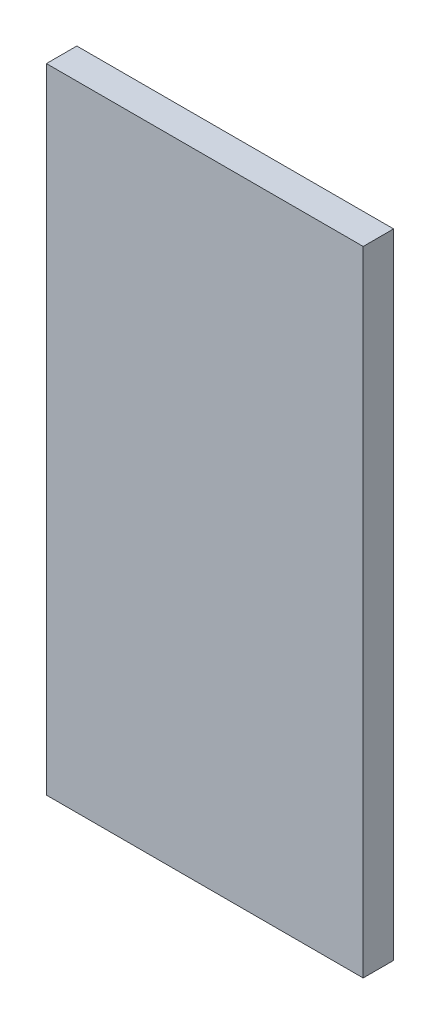
SolidWorks part; units mm, degrees
ref_plane "Front Plane" through (0, 0, 0) normal (0, 0, 1) x (1, 0, 0)
ref_plane "Top Plane" through (0, 0, 0) normal (0, 1, 0) x (1, 0, 0)
ref_plane "Right Plane" through (0, 0, 0) normal (1, 0, 0) x (0, 0, -1)
sketch "Sketch1" plane through (0, 0, 0) normal (0, 0, 1) x (1, 0, 0)
  line L1 (-25, 50) -> (25, 50)
  line L2 (-25, 50) -> (-25, -50)
  line L3 (-25, -50) -> (25, -50)
  line L4 (25, 50) -> (25, -50)
  line L5 (-25, 50) -> (25, -50) construction
  line L6 (-25, -50) -> (25, 50) construction
  point P0 (0, 0)
  dimension "D1" = 50
  dimension "D2" = 100
extrude "Boss-Extrude1" add sketch "Sketch1" along normal blind 4.8
